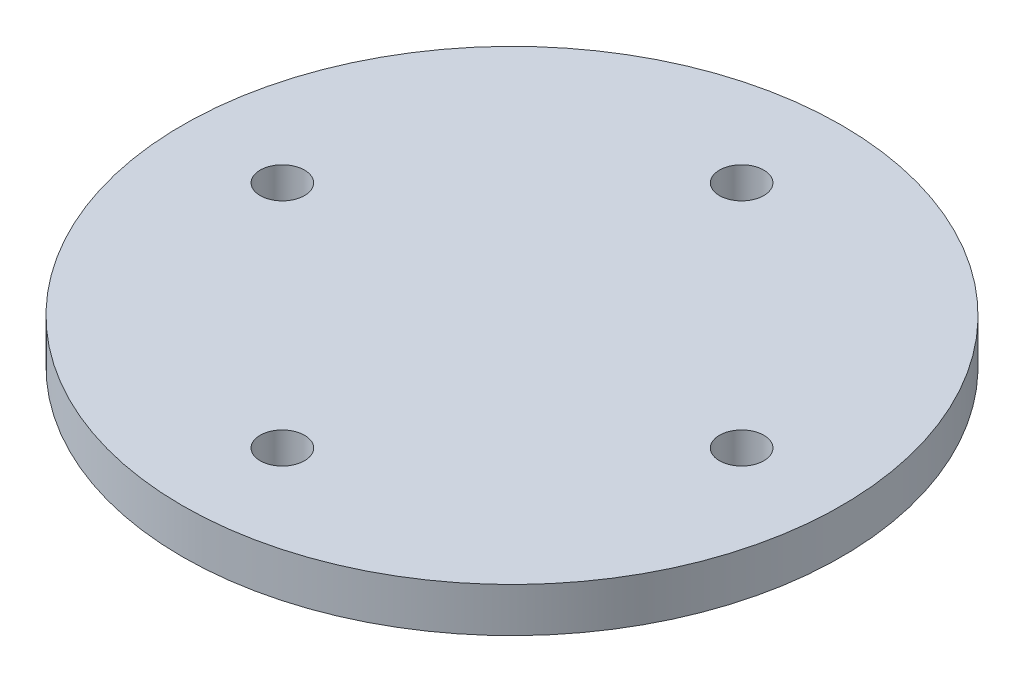
SolidWorks part; units mm, degrees
ref_plane "Front Plane" through (0, 0, 0) normal (0, 0, 1) x (1, 0, 0)
ref_plane "Top Plane" through (0, 0, 0) normal (0, 1, 0) x (1, 0, 0)
ref_plane "Right Plane" through (0, 0, 0) normal (1, 0, 0) x (0, 0, -1)
sketch "Sketch1" plane through (0, 0, 0) normal (0, 1, 0) x (1, 0, 0)
  circle A0 centre (0, 0) radius 14.875
  dimension "D1" = 29.75
extrude "Boss-Extrude1" add sketch "Sketch1" along normal blind 2
sketch "Sketch2" plane through (0, 2, 0) normal (0, 1, 0) x (1, 0, 0)
  circle A0 centre (0, 10.365) radius 1.7231
  circle A1 centre (10.365, 0) radius 1.7231
  circle A2 centre (0, -10.365) radius 1.7231
  circle A3 centre (-10.365, 0) radius 1.7231
  point P0 (0, 10.365)
  point P6 (10.365, 0)
  point P8 (0, -10.365)
  point P10 (-10.365, 0)
  point P12 (0, 0)
  dimension "D1" = 10.365
  dimension "D2" = 4
hole_wizard "Ø2.0mm Dowel Hole1" positions "Sketch2" profile "Sketch3" hole size "Ø2.0" standard "ANSI Metric"
sketch "Sketch3" plane through (0, 2, -10.365) normal (1, 0, 0) x (0, 0, 1)
  line L0 (0, 0) -> (0, 43.5309)
  line L1 (0, 43.5309) -> (1, 42.93)
  line L2 (1, 42.93) -> (1, 0)
  line L5 (1, 0) -> (0, 0)
  line L10 (0, 43.5309) -> (-1, 42.93) construction
  line L11 (0, -6.35) -> (0, 107.95) construction
  dimension "Hole Dia." = 2
  dimension "Hole Depth" = 42.93
  dimension "Drill Angle" = 118
chamfer "Chamfer1" distance 0.5 angle 45 4 edges at (10.365, 0, 1) (0, 0, 11.365) (0, 0, -9.365) (-10.365, 0, 1)
